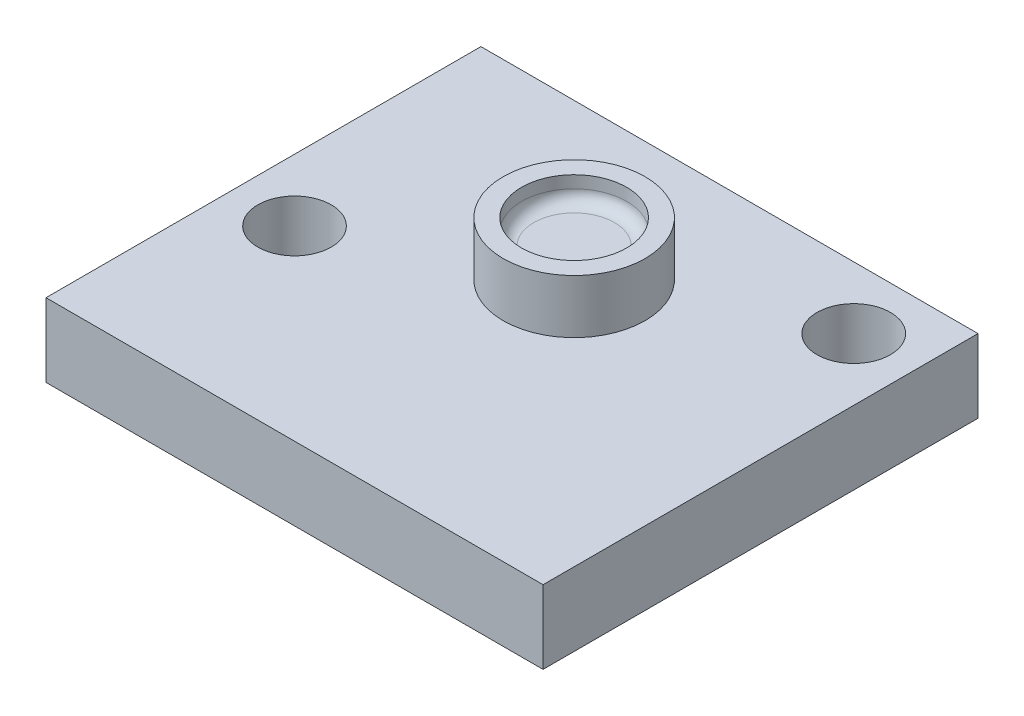
SolidWorks part; units mm, degrees
ref_plane "Front Plane" through (0, 0, 0) normal (0, 0, 1) x (1, 0, 0)
ref_plane "Top Plane" through (0, 0, 0) normal (0, 1, 0) x (1, 0, 0)
ref_plane "Right Plane" through (0, 0, 0) normal (1, 0, 0) x (0, 0, -1)
sketch "Sketch2" plane through (0, 0, 0) normal (0, 1, 0) x (1, 0, 0)
  line L1 (-10.16, -8.89) -> (10.16, -8.89)
  line L2 (-10.16, -8.89) -> (-10.16, 8.89)
  line L3 (-10.16, 8.89) -> (10.16, 8.89)
  line L4 (10.16, -8.89) -> (10.16, 8.89)
  line L5 (-10.16, -8.89) -> (10.16, 8.89) construction
  line L6 (-10.16, 8.89) -> (10.16, -8.89) construction
  line L7 (-10.16, -8.89) -> (-7.62, -8.89)
  line L8 (-10.16, -8.89) -> (-10.16, -1.27)
  line L9 (-10.16, -1.27) -> (-7.62, -1.27)
  line L10 (-7.62, -8.89) -> (-7.62, -1.27)
  line L11 (-10.16, -8.89) -> (0, -8.89)
  line L12 (-10.16, -8.89) -> (-10.16, 2.54)
  line L13 (-10.16, 2.54) -> (0, 2.54)
  line L14 (0, -8.89) -> (0, 2.54)
  line L15 (-10.16, -8.89) -> (7.62, -8.89)
  line L16 (-10.16, -8.89) -> (-10.16, 6.35)
  line L17 (-10.16, 6.35) -> (7.62, 6.35)
  line L18 (7.62, -8.89) -> (7.62, 6.35)
  circle A0 centre (-7.62, -1.27) radius 1.5
  circle A1 centre (0, 2.54) radius 2.9
  circle A2 centre (7.62, 6.35) radius 1.5
  point P0 (0, 0)
  dimension "D5" = 3
  dimension "D10" = 5.8
  dimension "D11" = 3
  dimension "D1" = 20.32
  dimension "D2" = 17.78
  dimension "D3" = 2.54
  dimension "D4" = 7.62
  dimension "D6" = 10.16
  dimension "D7" = 11.43
  dimension "D8" = 17.78
  dimension "D9" = 15.24
extrude "Boss-Extrude1" add sketch "Sketch2" along normal blind 3 contours A2 L17 L2 L13 A1 L14 L1 L18 | A1 L13 L2 L9 A0 L10 L1 L14 | A0 L9 L2 L1 L10
sketch "Sketch3" plane through (0, 3, 0) normal (0, 1, 0) x (1, 0, 0)
  circle A0 centre (0, 2.54) radius 2.9
  dimension "D1" = 5.8
extrude "Boss-Extrude2" add sketch "Sketch3" along normal blind 2.2
sketch "Sketch4" plane through (0, 5.2, 0) normal (0, 1, 0) x (1, 0, 0)
  circle A0 centre (0, 2.54) radius 2.15
  dimension "D1" = 4.3
extrude "Cut-Extrude1" cut sketch "Sketch4" against normal blind 1
fillet "Fillet2" radius 0.5 1 edges at (0, 4.2, -0.39)
